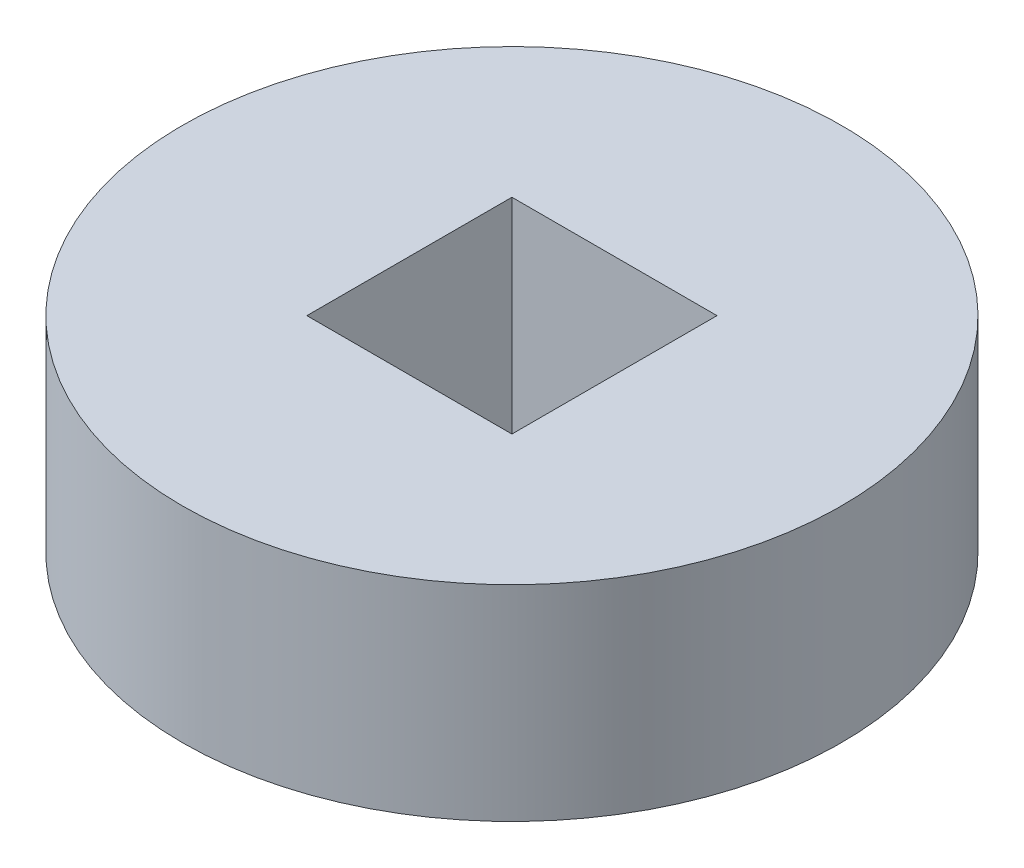
SolidWorks part; units mm, degrees
ref_plane "Front Plane" through (0, 0, 0) normal (0, 0, 1) x (1, 0, 0)
ref_plane "Top Plane" through (0, 0, 0) normal (0, 1, 0) x (1, 0, 0)
ref_plane "Right Plane" through (0, 0, 0) normal (1, 0, 0) x (0, 0, -1)
sketch "Elevator Support Pulleys" plane through (0, 0, 0) normal (0, 1, 0) x (1, 0, 0)
  line L1 (-3.175, 3.175) -> (3.175, 3.175)
  line L2 (-3.175, 3.175) -> (-3.175, -3.175)
  line L3 (-3.175, -3.175) -> (3.175, -3.175)
  line L4 (3.175, 3.175) -> (3.175, -3.175)
  line L5 (-3.175, 3.175) -> (3.175, -3.175) construction
  line L6 (-3.175, -3.175) -> (3.175, 3.175) construction
  circle A0 centre (0, 0) radius 10.2051
  dimension "D1" = 20.4103
  dimension "D2" = 6.35
  dimension "D3" = 6.35
extrude "Boss-Extrude1" add sketch "Elevator Support Pulleys" along normal blind 6.35
equation "\"Ball Diameter\"= 1.75in"
equation "\"Sheet Thickness\"= 0.25in"
equation "\"Screw Diameter\"= .17in"
equation "\"Robot Diameter\"= 14in"
equation "\"Castor Screw Diameter\"= 0.22in"
equation "\"Wheel Diameter\" = 4in"
equation "\"Nut Diameter\" = 8.4mm"
equation "\"Nut Height\" = 2.9mm"
equation "\"Screw Height\" = 0.55in"
equation "\"Pulley Diameter\" = 1in"
equation "\"Reactor Height\" = 14in"
equation "\"Elevator Height\" = 11.5in"
equation "\"Elevator Width\" = \"Ball Diameter\" + 0.25in"
equation "\"Elevator Axle Length\" = \"Elevator Width\" + 6*\"Sheet Thickness\""
equation "\"D1@Elevator Support Pulleys\"=\"Elevator Axle Endcap Diameter\""
equation "\"D2@Elevator Support Pulleys\"=\"Sheet Thickness\""
equation "\"D3@Elevator Support Pulleys\"=\"Sheet Thickness\""
equation "\"D1@Boss-Extrude1\"=\"Sheet Thickness\""
equation "\"Elevator Bearing Diameter\" = sqr(2*(\"Sheet Thickness\"^2)) + 0.2in"
equation "\"Elevator Axle Endcap Diameter\" = \"Elevator Bearing Diameter\" + 0.25in"
